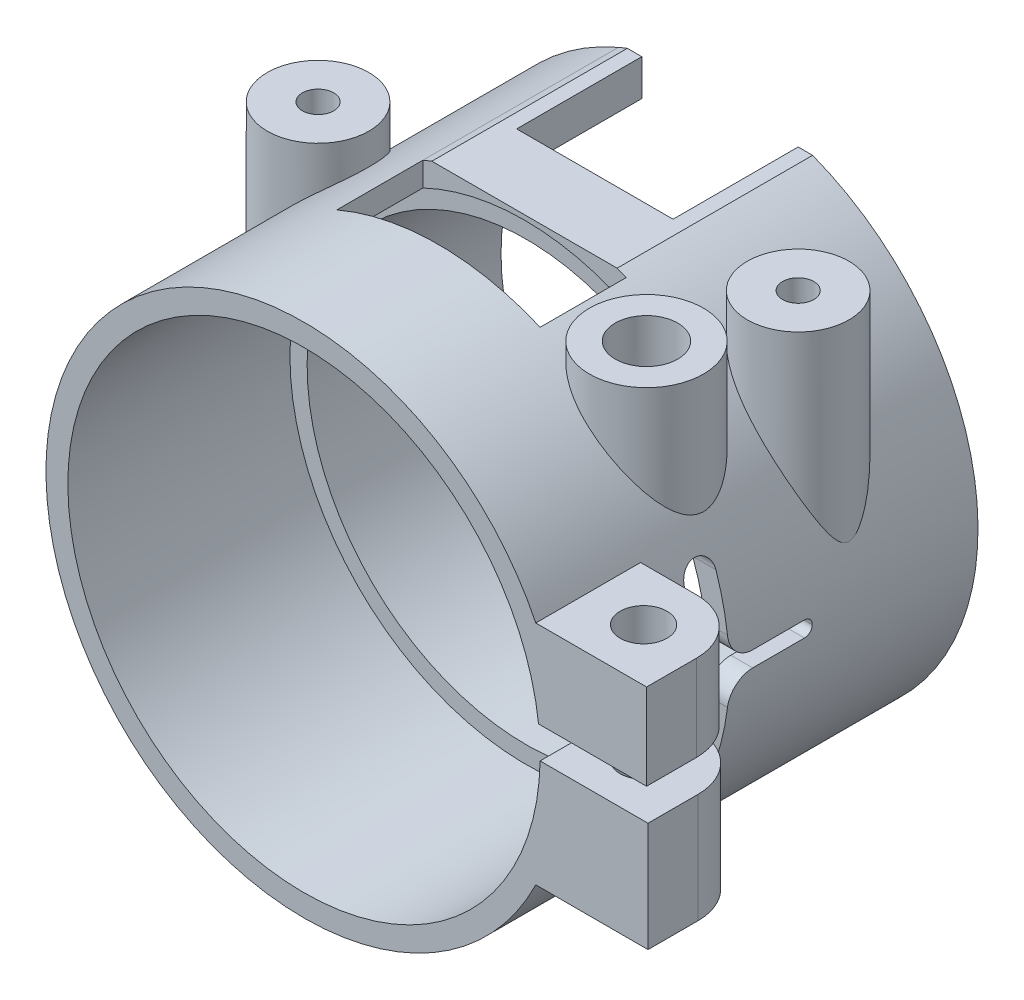
SolidWorks part; units mm, degrees
ref_plane "Alzado" through (0, 0, 0) normal (0, 0, 1) x (1, 0, 0)
ref_plane "Planta" through (0, 0, 0) normal (0, 1, 0) x (1, 0, 0)
ref_plane "Vista lateral" through (0, 0, 0) normal (1, 0, 0) x (0, 0, -1)
sketch "Croquis1" plane through (0, 0, 0) normal (0, 0, 1) x (1, 0, 0)
  circle A0 centre (0, 0) radius 16.5
  circle A1 centre (0, 0) radius 14
  dimension "D1" = 33
  dimension "D2" = 28
extrude "Saliente-Extruir1" add sketch "Croquis1" along normal blind 12.4
sketch "Croquis2" plane through (0, 0, 12.4) normal (0, 0, 1) x (1, 0, 0)
  circle A0 centre (0, 0) radius 16.5
  circle A1 centre (0, 0) radius 15.1
  dimension "D1" = 30.2
extrude "Saliente-Extruir2" add sketch "Croquis2" along normal blind 14.2
sketch "Croquis6" plane through (0, 0, 0) normal (0, 0, -1) x (-1, 0, 0)
  line L1 (-5, 16.5) -> (5, 16.5)
  line L2 (-5, 16.5) -> (-5, 13.0767)
  line L3 (-5, 13.0767) -> (5, 13.0767)
  line L4 (5, 16.5) -> (5, 13.0767)
  circle A0 centre (0, 0) radius 14 construction
  circle A1 centre (0, 0) radius 16.5 construction
  point P4 (0, 16.5)
  dimension "D1" = 10
extrude "Cortar-Extruir4" cut sketch "Croquis6" against normal blind 8
sketch "Croquis7" plane through (0, 0, 0) normal (0, 0, -1) x (-1, 0, 0)
  line L1 (-6.25, 16.5) -> (6.25, 16.5)
  line L2 (-6.25, 16.5) -> (-6.25, 15.4)
  line L3 (-6.25, 15.4) -> (6.25, 15.4)
  line L4 (6.25, 16.5) -> (6.25, 15.4)
  arc A0 (5, 15.7242) -> (-5, 15.7242) centre (0, 0) ccw construction
  point P8 (0, 16.5)
  dimension "D1" = 12.5
  dimension "D2" = 1.1
extrude "Cortar-Extruir5" cut sketch "Croquis7" against normal blind 18 contours L2 L1 L4 L3
sketch "Croquis8" plane through (0, 15.4, 0) normal (0, 1, 0) x (1, 0, 0)
  line L0 (5.9237, -18) -> (-5.9237, -18) construction
  line L1 (6.5, -18) -> (-6.5, -18)
  line L2 (6.5, -18) -> (6.5, -12.5)
  line L3 (6.5, -12.5) -> (-6.5, -12.5)
  line L4 (-6.5, -18) -> (-6.5, -12.5)
  line L5 (5, -8) -> (-5, -8) construction
  point P6 (0, -12.5)
  point P9 (0, -8)
  dimension "D1" = 13
  dimension "D2" = 5.5
extrude "Cortar-Extruir6" cut sketch "Croquis8" against normal up to next
sketch "Croquis9" plane through (0, 15.4, 0) normal (0, 1, 0) x (1, 0, 0)
  line L0 (-15.1, -26.6) -> (15.1, -26.6) construction
  line L1 (6.5, -18) -> (6.5, -12.5) construction
  line L2 (5, -8) -> (5, 0) construction
  circle A0 centre (10.9, -15.6) radius 2
  circle A1 centre (12.95, -7.95) radius 1
  circle A2 centre (-12.85, -12.85) radius 1
  circle A3 centre (10.9, -15.6) radius 3.65
  circle A4 centre (12.95, -7.95) radius 3.25
  circle A5 centre (-12.85, -12.85) radius 3.25
  dimension "D1" = 4
  dimension "D2" = 2
  dimension "D3" = 11
  dimension "D4" = 4.4
  dimension "D5" = 7.3
  dimension "D6" = 6.5
  dimension "D7" = 7.65
  dimension "D8" = 7.95
  dimension "D9" = 25.8
  dimension "D10" = 4.9
extrude "Saliente-Extruir3" add sketch "Croquis9" against normal up to next
sketch "Croquis10" plane through (0, 15.4, 0) normal (0, 1, 0) x (1, 0, 0)
  circle A0 centre (10.9, -15.6) radius 2
extrude "Cortar-Extruir7" cut sketch "Croquis10" against normal up to next
ref_plane "Plano2" through (20, 0, 0) normal (1, 0, 0) x (0, 0, -1)
sketch "Croquis11" plane through (20, 0, 0) normal (1, 0, 0) x (0, 0, -1)
  line L0 (-26.6, 1.75) -> (-19.4, 1.75)
  line L1 (-26.6, 16.5) -> (-26.6, -16.5) construction
  line L2 (-17.9, 3.25) -> (-17.9, 5.26)
  line L3 (-16.91, 6.25) -> (-16.89, 6.25)
  line L4 (-15.9, 5.26) -> (-15.9, 2)
  line L5 (-14.4, 0.5) -> (-11.09, 0.5)
  line L6 (-10.6, 0.01) -> (-10.6, -0.01)
  line L7 (-11.09, -0.5) -> (-14.4, -0.5)
  line L8 (-15.9, -2) -> (-15.9, -5.26)
  line L9 (-16.89, -6.25) -> (-16.91, -6.25)
  line L10 (-17.9, -5.26) -> (-17.9, -3.25)
  line L11 (-19.4, -1.75) -> (-26.6, -1.75)
  line L12 (-26.6, -1.75) -> (-26.6, 1.75)
  arc A0 (-15.9, 2) -> (-14.4, 0.5) centre (-14.4, 2) ccw
  arc A1 (-14.4, -0.5) -> (-15.9, -2) centre (-14.4, -2) ccw
  arc A2 (-17.9, -3.25) -> (-19.4, -1.75) centre (-19.4, -3.25) ccw
  arc A3 (-17.9, 3.25) -> (-19.4, 1.75) centre (-19.4, 3.25) cw
  arc A4 (-16.89, -6.25) -> (-15.9, -5.26) centre (-16.89, -5.26) ccw
  arc A5 (-16.91, -6.25) -> (-17.9, -5.26) centre (-16.91, -5.26) cw
  arc A6 (-16.89, 6.25) -> (-15.9, 5.26) centre (-16.89, 5.26) cw
  arc A7 (-16.91, 6.25) -> (-17.9, 5.26) centre (-16.91, 5.26) ccw
  arc A8 (-10.6, -0.01) -> (-11.09, -0.5) centre (-11.09, -0.01) cw
  arc A9 (-10.6, 0.01) -> (-11.09, 0.5) centre (-11.09, 0.01) ccw
  point P15 (-10.6, 0)
  point P17 (-26.6, 0)
  point P25 (-17.9, 1.75)
  point P32 (-15.9, 6.25)
  point P35 (-17.9, 6.25)
  point P38 (-10.6, -0.5)
  point P41 (-10.6, 0.5)
  dimension "D6" = 1.5
  dimension "D9" = 0.99
  dimension "D10" = 0.49
  dimension "D1" = 12.5
  dimension "D2" = 6.25
  dimension "D3" = 2
  dimension "D4" = 1
  dimension "D5" = 3.5
  dimension "D7" = 8.7
  dimension "D8" = 16
extrude "Cortar-Extruir8" cut sketch "Croquis11" against normal up to next
sketch "Croquis12" plane through (0, 0, 26.6) normal (0, 0, 1) x (1, 0, 0)
  line L0 (14.8219, 7.25) -> (21.9071, 7.25)
  line L1 (21.9071, 7.25) -> (21.9071, 1.75)
  line L2 (21.9071, 1.75) -> (16.4069, 1.75)
  line L3 (14.9982, 1.75) -> (16.4069, 1.75) construction
  line L4 (16.4981, -0.25) -> (21.9982, -0.25)
  line L5 (21.9982, -0.25) -> (21.9982, -7.25)
  line L6 (21.9982, -7.25) -> (14.8219, -7.25)
  line L7 (16.4981, -0.25) -> (15.0979, -0.25)
  line L8 (14.9982, -1.75) -> (16.4069, -1.75)
  arc A0 (16.4069, 1.75) -> (16.4069, -1.75) centre (0, 0) ccw construction
  arc A1 (14.8219, 7.25) -> (16.4069, 1.75) centre (0, 0) cw
  arc A2 (16.5, -0.01) -> (16.5, 0.01) centre (0, 0) ccw construction
  arc A3 (16.4069, -1.75) -> (14.8219, -7.25) centre (0, 0) cw
  arc A4 (14.9982, -1.75) -> (15.0979, -0.25) centre (0, 0) ccw
  dimension "D1" = 5.5
  dimension "D2" = 1.5
  dimension "D3" = 7
  dimension "D4" = 7
extrude "Saliente-Extruir4" add sketch "Croquis12" against normal blind 6.7
fillet "Redondeo1" radius 3.5 2 edges at (21.9982, -3.75, 19.9) (21.9071, 4.5, 19.9)
sketch "Croquis13" plane through (0, 7.25, 0) normal (0, 1, 0) x (1, 0, 0)
  line L0 (21.9071, -26.6) -> (14.8219, -26.6) construction
  line L1 (14.8219, -19.9) -> (14.8219, -26.6) construction
  circle A0 centre (18.3645, -23.25) radius 1.5
  point P5 (18.3645, -26.6)
  point P11 (14.8219, -23.25)
  dimension "D1" = 3
extrude "Cortar-Extruir9" cut sketch "Croquis13" against normal through all
equation "\"D2@Croquis11\"=\"D1@Croquis11\"/2"
